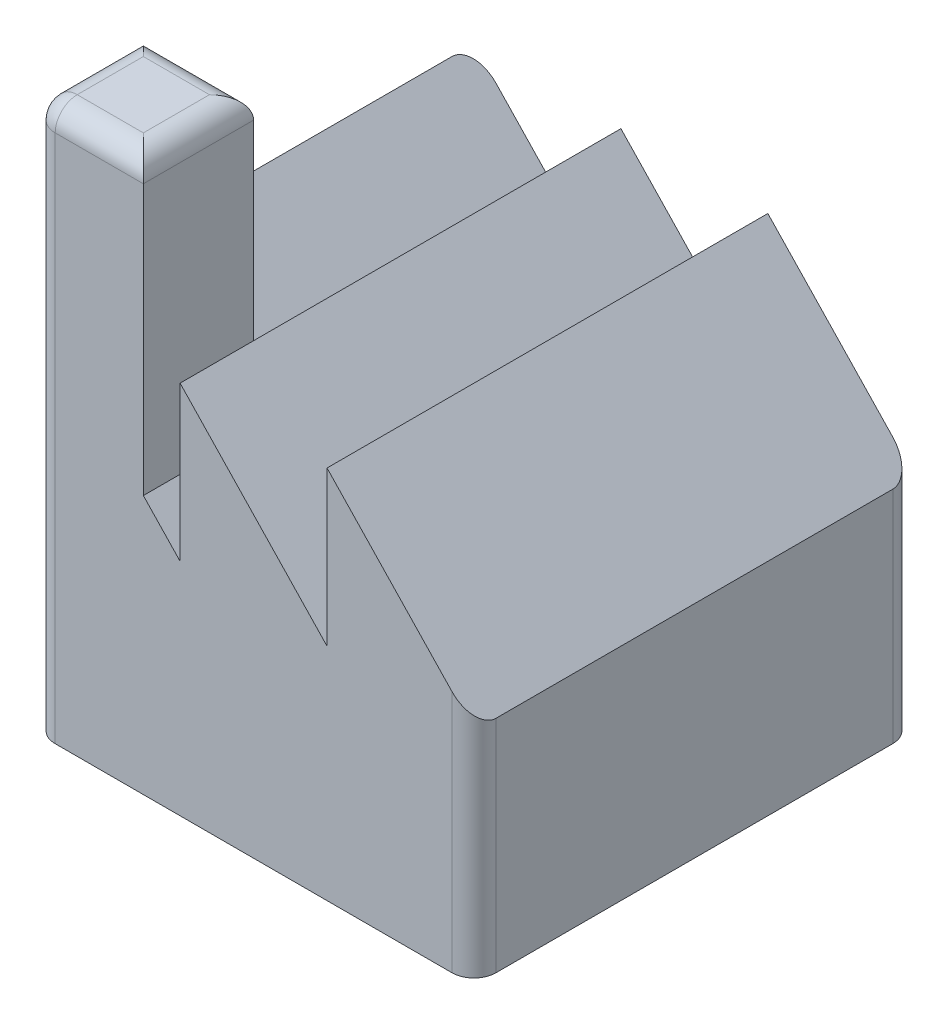
SolidWorks part; units mm, degrees
ref_plane "前视基准面" through (0, 0, 0) normal (0, 0, 1) x (1, 0, 0)
ref_plane "上视基准面" through (0, 0, 0) normal (0, 1, 0) x (1, 0, 0)
ref_plane "右视基准面" through (0, 0, 0) normal (1, 0, 0) x (0, 0, -1)
sketch "草图1" plane through (0, 0, 0) normal (0, 0, 1) x (1, 0, 0)
  line L0 (-10, 5) -> (-10, 12)
  line L1 (-10, -5) -> (10, -5)
  line L2 (-10, -5) -> (-10, 5)
  line L4 (10, -5) -> (10, 5)
  line L5 (-10, -5) -> (10, 5) construction
  line L6 (-10, 5) -> (10, -5) construction
  line L7 (-10, 12) -> (-3.3333, 5)
  line L8 (-3.3333, 5) -> (-3.3333, 12)
  line L9 (-3.3333, 12) -> (3.3333, 5)
  line L10 (3.3333, 5) -> (3.3333, 12)
  line L11 (3.3333, 12) -> (10, 5)
  line L12 (-10, 5) -> (-3.3333, 5) construction
  line L13 (3.3333, 5) -> (-3.3333, 5) construction
  line L14 (3.3333, 5) -> (10, 5) construction
  point P0 (0, 0)
  dimension "D1" = 10
  dimension "D2" = 20
  dimension "D3" = 7
extrude "凸台-拉伸1" add sketch "草图1" along normal blind 20
sketch "草图2" plane through (0, -5, 0) normal (0, -1, 0) x (1, 0, 0)
  line L1 (-10, 20) -> (-5, 20)
  line L2 (-10, 20) -> (-10, 15)
  line L3 (-10, 15) -> (-5, 15)
  line L4 (-5, 20) -> (-5, 15)
  dimension "D1" = 5
extrude "凸台-拉伸2" add sketch "草图2" against normal blind 25
sketch3d "3D草图1"
  line L0 (-7.5, 20, 17.5) -> (-7.5, 35, 17.5) construction
  line L1 (-10, 20, 15) -> (-5, 20, 20) construction
  line L6 (-10, 20, 15) -> (-10, 20, 20)
  line L7 (-10, 20, 20) -> (-5, 20, 20)
  line L8 (-5, 20, 20) -> (-5, 20, 15)
  line L9 (-5, 20, 15) -> (-10, 20, 15)
  line L10 (-10, 20, 15) -> (-10, 20, 20)
  line L11 (-10, 20, 20) -> (-5, 20, 20)
  line L12 (-5, 20, 20) -> (-5, 20, 15)
  line L13 (-5, 20, 15) -> (-10, 20, 15)
  circle A0 centre (-7.5, 35, 17.5) radius 3.75
  point P8 (-7.5, 38.75, 17.5)
  dimension "D1" = 7.5
  dimension "D2" = 15
  dimension "D3" = 0
loft "放样1" [suppressed] add
fillet "圆角1" radius 1 8 edges at (-7.5, 20, 15) (-5, 20, 17.5) (-7.5, 20, 20) (-10, 20, 17.5) (-10, 3.5, 0) (-10, 7.5, 20) (10, 0, 20) (10, 0, 0)
